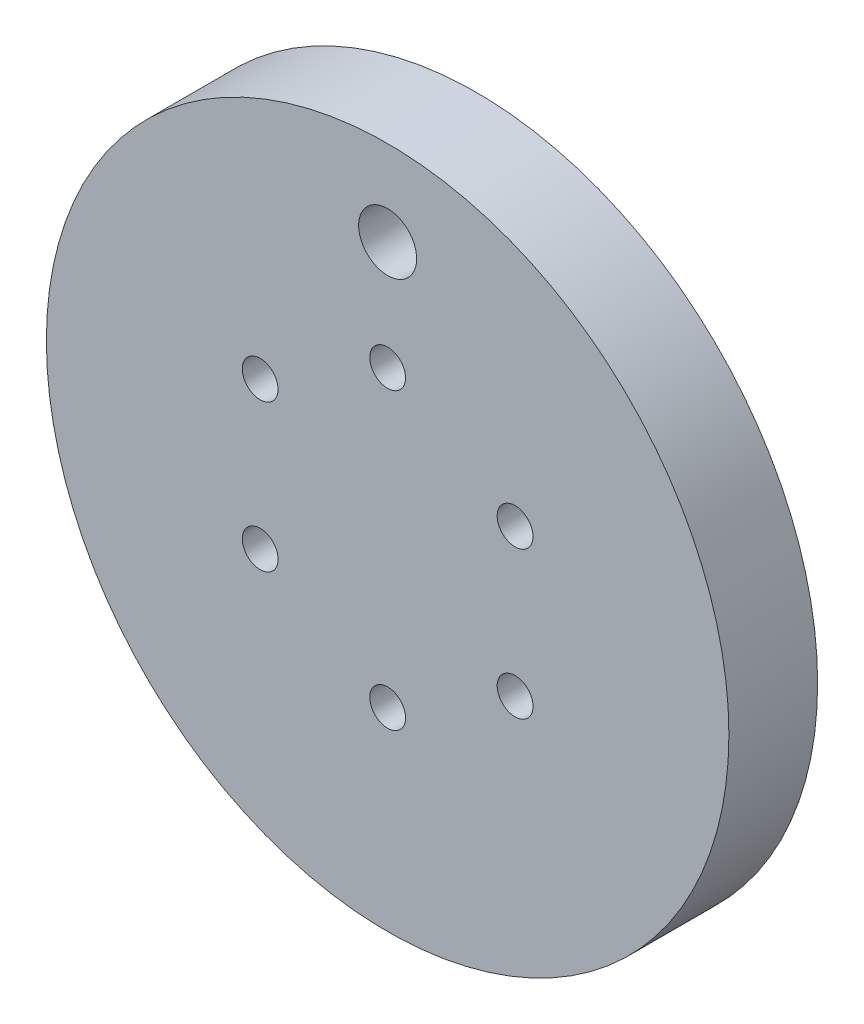
SolidWorks part; units mm, degrees
ref_plane "前视基准面" through (0, 0, 0) normal (0, 0, 1) x (1, 0, 0)
ref_plane "上视基准面" through (0, 0, 0) normal (0, 1, 0) x (1, 0, 0)
ref_plane "右视基准面" through (0, 0, 0) normal (1, 0, 0) x (0, 0, -1)
other "Configuration Table"
sketch "草图1" plane through (0, 0, 0) normal (0, 0, 1) x (1, 0, 0)
  circle A0 centre (0, 0) radius 40
  circle A1 centre (0, 17.25) radius 2.1
  circle A2 centre (14.9389, 8.625) radius 2.1
  circle A3 centre (14.9389, -8.625) radius 2.1
  circle A4 centre (0, -17.25) radius 2.1
  circle A5 centre (-14.9389, -8.625) radius 2.1
  circle A6 centre (-14.9389, 8.625) radius 2.1
  point P17 (0, 0)
  dimension "D1" = 80
  dimension "D2" = 4.2
  dimension "D3" = 17.25
  dimension "D4" = 6
extrude "凸台-拉伸1" add sketch "草图1" along normal blind 10.4 contours A0 | A6 | A5 | A4 | A3 | A2 | A1
sketch "草图2" plane through (0, 0, 10.4) normal (0, 0, 1) x (1, 0, 0)
  circle A0 centre (0, 30) radius 3.4
  circle A1 centre (0, 0) radius 40
  circle A2 centre (0, 0) radius 40
  dimension "D2" = 30
  dimension "D3" = 6.8
  dimension "D1" = 0
extrude "切除-拉伸1" cut sketch "草图2" against normal through all contours A0
